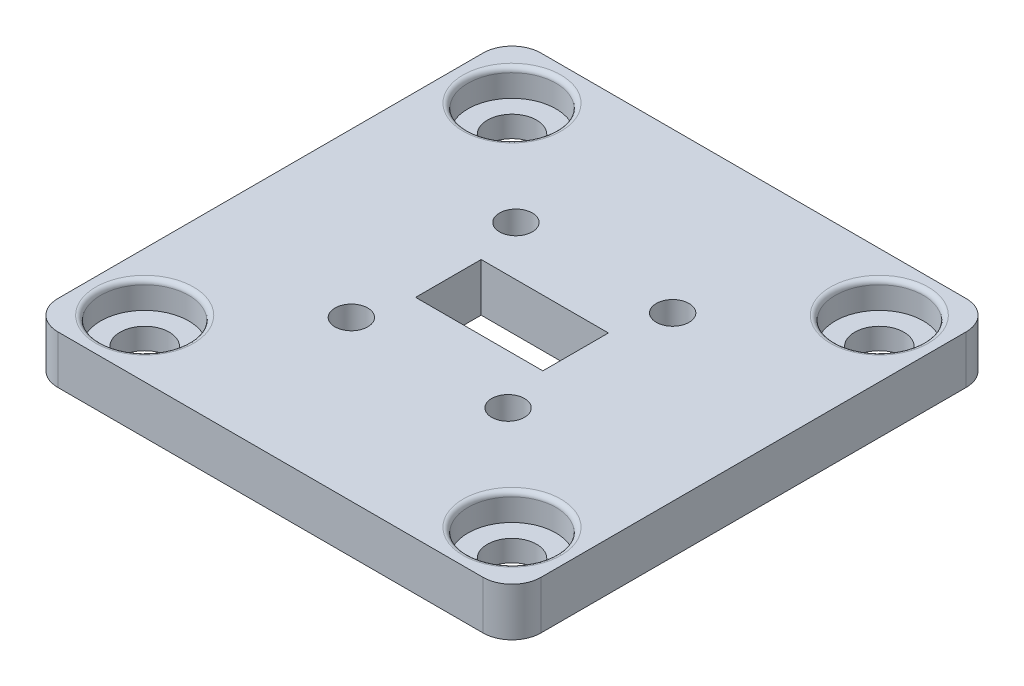
SolidWorks part; units mm, degrees
ref_plane "Front Plane" through (0, 0, 0) normal (0, 0, 1) x (1, 0, 0)
ref_plane "Top Plane" through (0, 0, 0) normal (0, 1, 0) x (1, 0, 0)
ref_plane "Right Plane" through (0, 0, 0) normal (1, 0, 0) x (0, 0, -1)
sketch "Sketch1" plane through (0, 0, 0) normal (0, 1, 0) x (1, 0, 0)
  line L0 (0, 0) -> (0, 8.3651) construction
  line L1 (-6.6, -3.4) -> (6.6, -3.4)
  line L2 (-6.6, -3.4) -> (-6.6, 3.4)
  line L3 (-6.6, 3.4) -> (6.6, 3.4)
  line L4 (6.6, -3.4) -> (6.6, 3.4)
  line L5 (-6.6, -3.4) -> (6.6, 3.4) construction
  line L6 (-6.6, 3.4) -> (6.6, -3.4) construction
  line L7 (-25.05, -25.05) -> (25.05, -25.05)
  line L8 (-25.05, -25.05) -> (-25.05, 25.05)
  line L9 (-25.05, 25.05) -> (25.05, 25.05)
  line L10 (25.05, -25.05) -> (25.05, 25.05)
  line L11 (-25.05, -25.05) -> (25.05, 25.05) construction
  line L12 (-25.05, 25.05) -> (25.05, -25.05) construction
  line L13 (0, 0) -> (13.798, 0) construction
  circle A0 centre (-19.05, 19.05) radius 2.5527
  circle A1 centre (19.05, 19.05) radius 2.5527
  circle A2 centre (19.05, -19.05) radius 2.5527
  circle A3 centre (-19.05, -19.05) radius 2.5527
  circle A4 centre (-8.128, 8.5344) radius 1.7
  circle A5 centre (8.128, 8.5344) radius 1.7
  circle A6 centre (8.128, -8.5344) radius 1.7
  circle A7 centre (-8.128, -8.5344) radius 1.7
  point P0 (0, 0)
  point P6 (0, 0)
  dimension "D3" = 38.1
  dimension "D4" = 38.1
  dimension "D5" = 5.1054
  dimension "D6" = 6
  dimension "D7" = 3.4
  dimension "D8" = 8.5344
  dimension "D9" = 8.128
  dimension "D1" = 6.8
  dimension "D2" = 13.2
extrude "Boss-Extrude1" add sketch "Sketch1" along normal blind 5 contours L7 L10 L9 L8 A5 A4 A1 A0 L4 L1 L2 L3 A2 A3 A6 A7
fillet "Fillet1" radius 3 4 edges at (25.05, 2.5, 25.05) (-25.05, 2.5, 25.05) (25.05, 2.5, -25.05) (-25.05, 2.5, -25.05)
sketch "Sketch2" plane through (0, 0, 0) normal (0, -1, 0) x (1, 0, 0)
  line L1 (-8.128, 11.7098) -> (-10.878, 10.1221)
  line L2 (-10.878, 10.1221) -> (-10.878, 6.9467)
  line L3 (-10.878, 6.9467) -> (-8.128, 5.359)
  line L4 (-8.128, 5.359) -> (-5.378, 6.9467)
  line L5 (-5.378, 6.9467) -> (-5.378, 10.1221)
  line L6 (-5.378, 10.1221) -> (-8.128, 11.7098)
  line L7 (8.128, 11.7098) -> (5.378, 10.1221)
  line L8 (5.378, 10.1221) -> (5.378, 6.9467)
  line L9 (5.378, 6.9467) -> (8.128, 5.359)
  line L10 (8.128, 5.359) -> (10.878, 6.9467)
  line L11 (10.878, 6.9467) -> (10.878, 10.1221)
  line L12 (10.878, 10.1221) -> (8.128, 11.7098)
  line L13 (-8.128, -5.359) -> (-10.878, -6.9467)
  line L14 (-10.878, -6.9467) -> (-10.878, -10.1221)
  line L15 (-10.878, -10.1221) -> (-8.128, -11.7098)
  line L16 (-8.128, -11.7098) -> (-5.378, -10.1221)
  line L17 (-5.378, -10.1221) -> (-5.378, -6.9467)
  line L18 (-5.378, -6.9467) -> (-8.128, -5.359)
  line L19 (8.128, -5.359) -> (5.378, -6.9467)
  line L20 (5.378, -6.9467) -> (5.378, -10.1221)
  line L21 (5.378, -10.1221) -> (8.128, -11.7098)
  line L22 (8.128, -11.7098) -> (10.878, -10.1221)
  line L23 (10.878, -10.1221) -> (10.878, -6.9467)
  line L24 (10.878, -6.9467) -> (8.128, -5.359)
  circle A0 centre (-8.128, 8.5344) radius 2.75 construction
  circle A1 centre (8.128, 8.5344) radius 2.75 construction
  circle A2 centre (-8.128, -8.5344) radius 2.75 construction
  circle A3 centre (8.128, -8.5344) radius 2.75 construction
  dimension "D1" = 5.5
extrude "Cut-Extrude1" cut sketch "Sketch2" against normal blind 2.6
sketch "Sketch5" plane through (0, 5, 0) normal (0, 1, 0) x (1, 0, 0)
  circle A0 centre (-19.05, 19.05) radius 4.5675
  circle A1 centre (19.05, 19.05) radius 4.5675
  circle A2 centre (19.05, -19.05) radius 4.5675
  circle A3 centre (-19.05, -19.05) radius 4.5675
  dimension "D1" = 9.135
extrude "Cut-Extrude4" cut sketch "Sketch5" against normal offset from surface (2.8 mm away) 2.2 up to face at (8.128, 0, 8.5344)
fillet "Fillet2" radius 0.5 4 edges at (19.05, 5, 23.6175) (-19.05, 5, 23.6175) (19.05, 5, -14.4825) (-19.05, 5, -14.4825)
sketch "Sketch3" plane through (0, 5, 0) normal (0, 1, 0) x (1, 0, 0)
  line L0 (0, 0) -> (0, 6.6065) construction
  line L1 (0, 0) -> (8.9891, 0) construction
  line L3 (-6.6, -3.4) -> (-6.6, 3.4) construction
  line L4 (-3.4, 6.6) -> (3.4, 6.6)
  line L5 (-3.4, 6.6) -> (-3.4, -6.6)
  line L6 (-3.4, -6.6) -> (3.4, -6.6)
  line L7 (3.4, 6.6) -> (3.4, -6.6)
  line L8 (-3.4, 6.6) -> (3.4, -6.6) construction
  line L9 (-3.4, -6.6) -> (3.4, 6.6) construction
  line L10 (-6.6, 3.4) -> (6.6, 3.4) construction
  circle A0 centre (8.5344, 8.128) radius 1.7
  circle A1 centre (8.128, 8.5344) radius 1.7 construction
  circle A2 centre (-8.5344, 8.128) radius 1.7
  circle A3 centre (8.5344, -8.128) radius 1.7
  circle A4 centre (-8.5344, -8.128) radius 1.7
  dimension "D1" = 8.5344
  dimension "D2" = 8.128
extrude "Cut-Extrude2" [suppressed] cut sketch "Sketch3" against normal up to surface (5 mm away)
sketch "Sketch4" [suppressed] plane through (0, 0, 0) normal (0, -1, 0) x (1, 0, 0)
  line L0 (-5.378, 10.1221) -> (-8.128, 11.7098) construction
  line L1 (-8.5344, 11.3034) -> (-11.2844, 9.7157)
  line L2 (-11.2844, 9.7157) -> (-11.2844, 6.5403)
  line L3 (-11.2844, 6.5403) -> (-8.5344, 4.9526)
  line L4 (-8.5344, 4.9526) -> (-5.7844, 6.5403)
  line L5 (-5.7844, 6.5403) -> (-5.7844, 9.7157)
  line L6 (-5.7844, 9.7157) -> (-8.5344, 11.3034)
  line L7 (0, 0) -> (0, 3.4765) construction
  line L8 (0, 0) -> (4.0075, 0) construction
  line L9 (5.7844, 9.7157) -> (8.5344, 11.3034)
  line L10 (5.7844, 6.5403) -> (5.7844, 9.7157)
  line L11 (8.5344, 4.9526) -> (5.7844, 6.5403)
  line L12 (11.2844, 6.5403) -> (8.5344, 4.9526)
  line L13 (11.2844, 9.7157) -> (11.2844, 6.5403)
  line L14 (8.5344, 11.3034) -> (11.2844, 9.7157)
  line L15 (8.5344, -11.3034) -> (11.2844, -9.7157)
  line L16 (11.2844, -9.7157) -> (11.2844, -6.5403)
  line L17 (11.2844, -6.5403) -> (8.5344, -4.9526)
  line L18 (8.5344, -4.9526) -> (5.7844, -6.5403)
  line L19 (5.7844, -6.5403) -> (5.7844, -9.7157)
  line L20 (5.7844, -9.7157) -> (8.5344, -11.3034)
  line L21 (-5.7844, -9.7157) -> (-8.5344, -11.3034)
  line L22 (-5.7844, -6.5403) -> (-5.7844, -9.7157)
  line L23 (-8.5344, -4.9526) -> (-5.7844, -6.5403)
  line L24 (-11.2844, -6.5403) -> (-8.5344, -4.9526)
  line L25 (-11.2844, -9.7157) -> (-11.2844, -6.5403)
  line L26 (-8.5344, -11.3034) -> (-11.2844, -9.7157)
  circle A1 centre (-8.5344, 8.128) radius 1.7
  arc A2 (-9.516, 9.516) -> (-7.1464, 7.1464) centre (-8.5344, 8.128) ccw construction
  circle A3 centre (-8.5344, 8.128) radius 2.75 construction
  circle A4 centre (8.5344, 8.128) radius 2.75 construction
  circle A5 centre (8.5344, -8.128) radius 2.75 construction
  circle A6 centre (-8.5344, -8.128) radius 2.75 construction
extrude "Cut-Extrude3" [suppressed] cut sketch "Sketch4" against normal up to surface (2.6 mm away)
